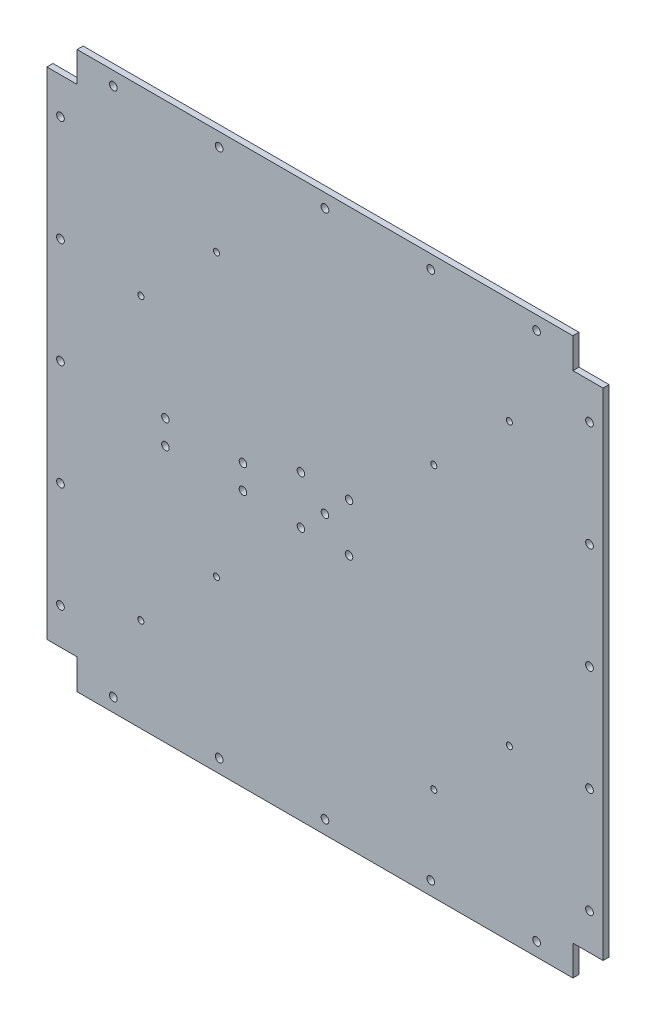
SolidWorks part; units mm, degrees
ref_plane "前视基准面" through (0, 0, 0) normal (0, 0, 1) x (1, 0, 0)
ref_plane "上视基准面" through (0, 0, 0) normal (0, 1, 0) x (1, 0, 0)
ref_plane "右视基准面" through (0, 0, 0) normal (1, 0, 0) x (0, 0, -1)
sketch "草图1" plane through (0, 0, 0) normal (0, 0, 1) x (1, 0, 0)
  line L1 (184, -184) -> (-184, -184)
  line L2 (184, -184) -> (184, 184)
  line L3 (184, 184) -> (-184, 184)
  line L4 (-184, -184) -> (-184, 184)
  line L5 (184, -184) -> (-184, 184) construction
  line L6 (184, 184) -> (-184, -184) construction
  point P0 (0, 0)
  dimension "D1" = 368
  dimension "D2" = 368
extrude "凸台-拉伸1" add sketch "草图1" along normal blind 4
sketch "草图3" plane through (0, 0, 4) normal (0, 0, 1) x (1, 0, 0)
  line L0 (0, -184) -> (0, -175) construction
  line L1 (-184, -184) -> (184, -184) construction
  circle A0 centre (0, -175) radius 2.55
  circle A1 centre (70, -175) radius 2.55
  circle A2 centre (140, -175) radius 2.55
  circle A3 centre (-70, -175) radius 2.55
  circle A4 centre (-140, -175) radius 2.55
  circle A30 centre (-175, 140) radius 2.55
  circle A31 centre (-175, 70) radius 2.55
  circle A32 centre (-175, -70) radius 2.55
  circle A33 centre (-175, -140) radius 2.55
  circle A34 centre (-175, 0) radius 2.55
  circle A35 centre (140, 175) radius 2.55
  circle A36 centre (70, 175) radius 2.55
  circle A37 centre (-70, 175) radius 2.55
  circle A38 centre (-140, 175) radius 2.55
  circle A39 centre (0, 175) radius 2.55
  circle A40 centre (175, -140) radius 2.55
  circle A41 centre (175, -70) radius 2.55
  circle A42 centre (175, 70) radius 2.55
  circle A43 centre (175, 140) radius 2.55
  circle A44 centre (175, 0) radius 2.55
  point P47 (10, -10)
  point P78 (0, 0)
  dimension "D1" = 5.1
  dimension "D2" = 9
  dimension "D3" = 3
  dimension "D4" = 3
  dimension "D6" = 4
extrude "切除-拉伸2" cut sketch "草图3" against normal through all
sketch "草图4" plane through (0, 0, 4) normal (0, 0, 1) x (1, 0, 0)
  line L0 (-164, 184) -> (-164, 164)
  line L1 (-184, -184) -> (-164, -184)
  line L2 (-184, -184) -> (-184, -164)
  line L3 (-184, -164) -> (-164, -164)
  line L4 (-164, -184) -> (-164, -164)
  line L5 (-184, 164) -> (-164, 164)
  line L6 (-184, 184) -> (-164, 184)
  line L7 (-184, 184) -> (-184, 164)
  line L8 (184, 164) -> (164, 164)
  line L9 (164, 184) -> (164, 164)
  line L10 (184, 184) -> (184, 164)
  line L11 (184, 184) -> (164, 184)
  line L12 (164, -184) -> (164, -164)
  line L13 (184, -164) -> (164, -164)
  line L14 (184, -184) -> (164, -184)
  line L15 (184, -184) -> (184, -164)
  point P20 (0, 0)
  dimension "D1" = 20
  dimension "D2" = 20
  dimension "D3" = 4
extrude "切除-拉伸3" cut sketch "草图4" against normal through all contours L0 L5 L7 L6 | L8 L9 L11 L10 | L12 L13 L15 L14 | L2 L1 L4 L3
sketch "草图5" plane through (0, 0, 4) normal (0, 0, 1) x (1, 0, 0)
  line L0 (-184, 0) -> (184, 0) construction
  line L1 (-184, 164) -> (-184, -164) construction
  line L3 (0, 184) -> (0, -184) construction
  line L4 (164, 184) -> (-164, 184) construction
  line L5 (-164, -184) -> (164, -184) construction
  line L6 (-10, 0) -> (-22.5, 0) construction
  line L11 (10, -10) -> (-10, 10) construction
  line L12 (10, 10) -> (-10, -10) construction
  line L13 (0, -10) -> (0, -22.5) construction
  line L14 (10, 0) -> (22.5, 0) construction
  line L15 (0, 10) -> (0, 22.5) construction
  line L16 (-173.9781, 173.9781) -> (0, 0) construction
  line L17 (-184, 0) -> (0, 184) construction
  line L18 (0, 0) -> (-15.9099, 15.9099) construction
  line L19 (-14.489, 14.489) -> (-159.489, 14.489) construction
  line L20 (-14.489, 14.489) -> (-14.489, 159.489) construction
  line L21 (-14.489, 159.489) -> (-159.489, 159.489) construction
  line L22 (-159.489, 14.489) -> (-159.489, 159.489) construction
  line L23 (-14.489, 14.489) -> (-159.489, 159.489) construction
  line L24 (-14.489, 159.489) -> (-159.489, 14.489) construction
  line L25 (0, 0) -> (15.9099, 15.9099) construction
  circle A4 centre (0, 0) radius 2.5
  circle A5 centre (-15.9099, 15.9099) radius 2.5
  circle A7 centre (15.9099, 15.9099) radius 2.5
  circle A8 centre (15.9099, -15.9099) radius 2.5
  circle A9 centre (-15.9099, -15.9099) radius 2.5
  point P4 (-86.989, 86.989)
  point P12 (0, 0)
  dimension "D11" = 5
  dimension "D16" = 5
  dimension "D17" = 5
  dimension "D1" = 20
  dimension "D2" = 20
  dimension "D3" = 12.5
  dimension "D4" = 12.5
  dimension "D5" = 12.5
  dimension "D6" = 12.5
  dimension "D12" = 145
  dimension "D13" = 145
  dimension "D14" = 22.5
  dimension "D15" = 22.5
extrude "切除-拉伸6" cut sketch "草图5" against normal blind 10
sketch "草图6" plane through (0, 0, 0) normal (0, 0, -1) x (-1, 0, 0)
  circle A0 centre (121.8, -122) radius 2
  circle A1 centre (71.8, -72) radius 2
  circle A2 centre (-72, -122) radius 2
  circle A3 centre (-122, -72) radius 2
  circle A4 centre (-72, 64) radius 2
  circle A5 centre (-122, 114) radius 2
  circle A6 centre (121.8, 64) radius 2.0451
  circle A7 centre (71.8, 114) radius 2
  circle A8 centre (105.5531, -14) radius 2.5
  circle A9 centre (105.5531, 2) radius 2.5
  circle A10 centre (54.2531, -14) radius 2.5
  circle A11 centre (54.2531, 2) radius 2.5
extrude "切除-拉伸7" cut sketch "草图6" against normal blind 10
